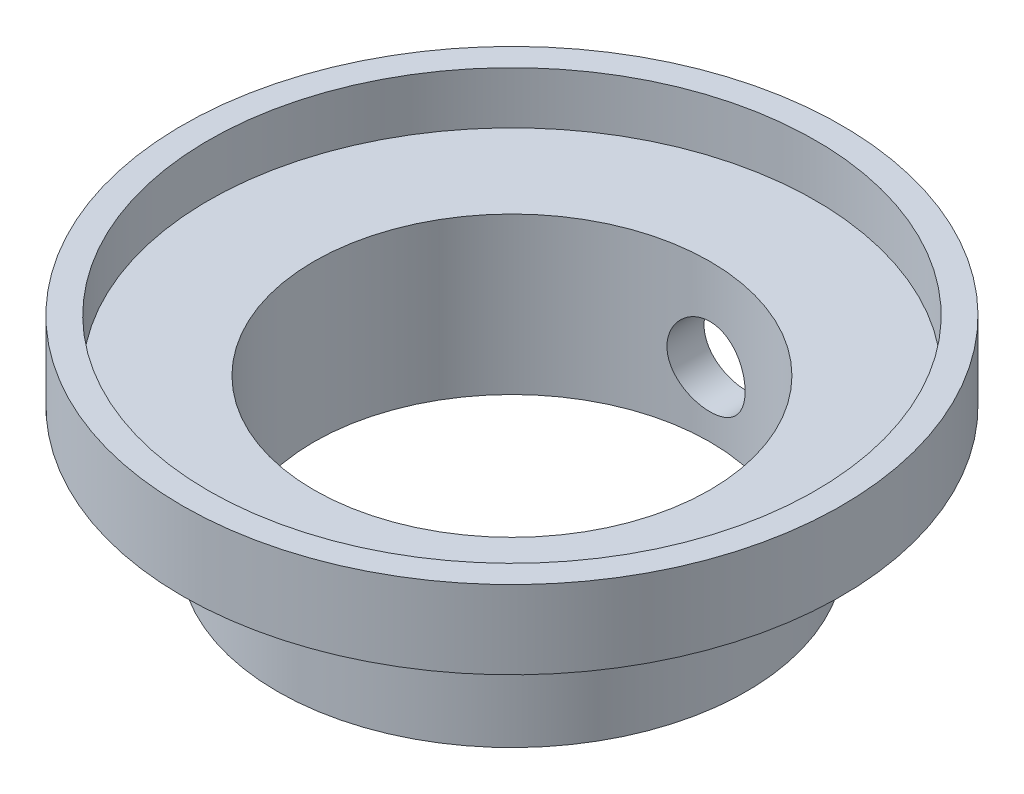
SolidWorks part; units mm, degrees
ref_plane "Plan de face" through (0, 0, 0) normal (0, 0, 1) x (1, 0, 0)
ref_plane "Plan de dessus" through (0, 0, 0) normal (0, 1, 0) x (1, 0, 0)
ref_plane "Plan de droite" through (0, 0, 0) normal (1, 0, 0) x (0, 0, -1)
sketch "Esquisse1" plane through (0, 0, 0) normal (0, 1, 0) x (1, 0, 0)
  circle A0 centre (0, 0) radius 7.6
  circle A1 centre (0, 0) radius 9
  dimension "D1" = 15.2
  dimension "D2" = 18
extrude "Boss.-Extru.1" add sketch "Esquisse1" along normal blind 5
sketch "Esquisse2" plane through (0, 5, 0) normal (0, 1, 0) x (1, 0, 0)
  circle A0 centre (0, 0) radius 7.6
  circle A1 centre (0, 0) radius 12.65
  dimension "D1" = 25.3
  dimension "D2" = 15.2
extrude "Boss.-Extru.2" add sketch "Esquisse2" along normal blind 3
sketch "Esquisse3" plane through (0, 8, 0) normal (0, 1, 0) x (1, 0, 0)
  circle A0 centre (0, 0) radius 11.65
  dimension "D1" = 23.3
extrude "Enlèv. mat.-Extru.1" cut sketch "Esquisse3" against normal blind 2
sketch "Esquisse4" plane through (0, 0, 0) normal (0, 0, 1) x (1, 0, 0)
  line L0 (0, 5) -> (0, 0) construction
  line L1 (-9, 5) -> (9, 5) construction
  line L2 (-9, 0) -> (9, 0) construction
  circle A0 centre (0, 2.5) radius 1.5
  dimension "D1" = 3
extrude "Enlèv. mat.-Extru.2" cut sketch "Esquisse4" against normal blind 12
